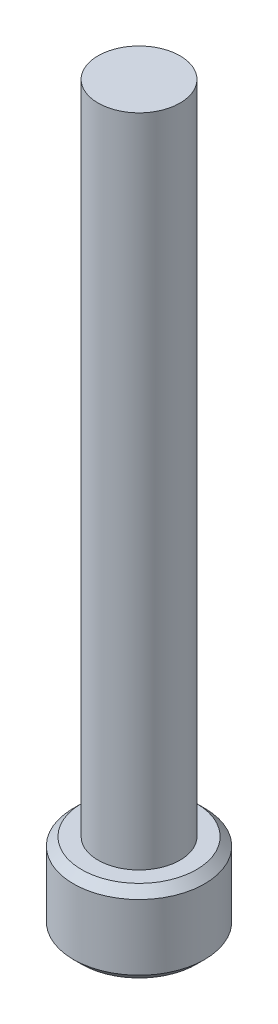
SolidWorks part; units mm, degrees
ref_plane "Front Plane" through (0, 0, 0) normal (0, 0, 1) x (1, 0, 0)
ref_plane "Top Plane" through (0, 0, 0) normal (0, 1, 0) x (1, 0, 0)
ref_plane "Right Plane" through (0, 0, 0) normal (1, 0, 0) x (0, 0, -1)
sketch "Sketch1" plane through (0, 0, 0) normal (0, 1, 0) x (1, 0, 0)
  circle A0 centre (0, 0) radius 2.5
extrude "Boss-Extrude1" add sketch "Sketch1" along normal blind 40
sketch "Sketch3" plane through (0, 0, 0) normal (0, 0, 1) x (1, 0, 0)
  line L0 (0, 0) -> (-4, 0)
  line L1 (-2.5, 0) -> (2.5, 0) construction
  line L2 (-4, 0) -> (-4, -5)
  line L3 (0, 0) -> (0, 12.6087) construction
  line L4 (-4, -5) -> (0, -5)
  line L5 (0, -5) -> (0, 0)
revolve "Revolve1" add sketch "Sketch3" angle 360 about L5
sketch "Sketch4" plane through (0, 0, 0) normal (0, 1, 0) x (1, 0, 0)
  line L1 (2.8868, 0) -> (1.4434, 2.5)
  line L2 (1.4434, 2.5) -> (-1.4434, 2.5)
  line L3 (-1.4434, 2.5) -> (-2.8868, 0)
  line L4 (-2.8868, 0) -> (-1.4434, -2.5)
  line L5 (-1.4434, -2.5) -> (1.4434, -2.5)
  line L6 (1.4434, -2.5) -> (2.8868, 0)
  circle A0 centre (0, 0) radius 2.5 construction
extrude "Cut-Extrude1" cut sketch "Sketch4" against normal blind 30 from offset 1 offset against normal yes
chamfer "Chamfer1" distance 0.5 angle 45 2 edges at (0, -5, -4) (0, 0, -4)
